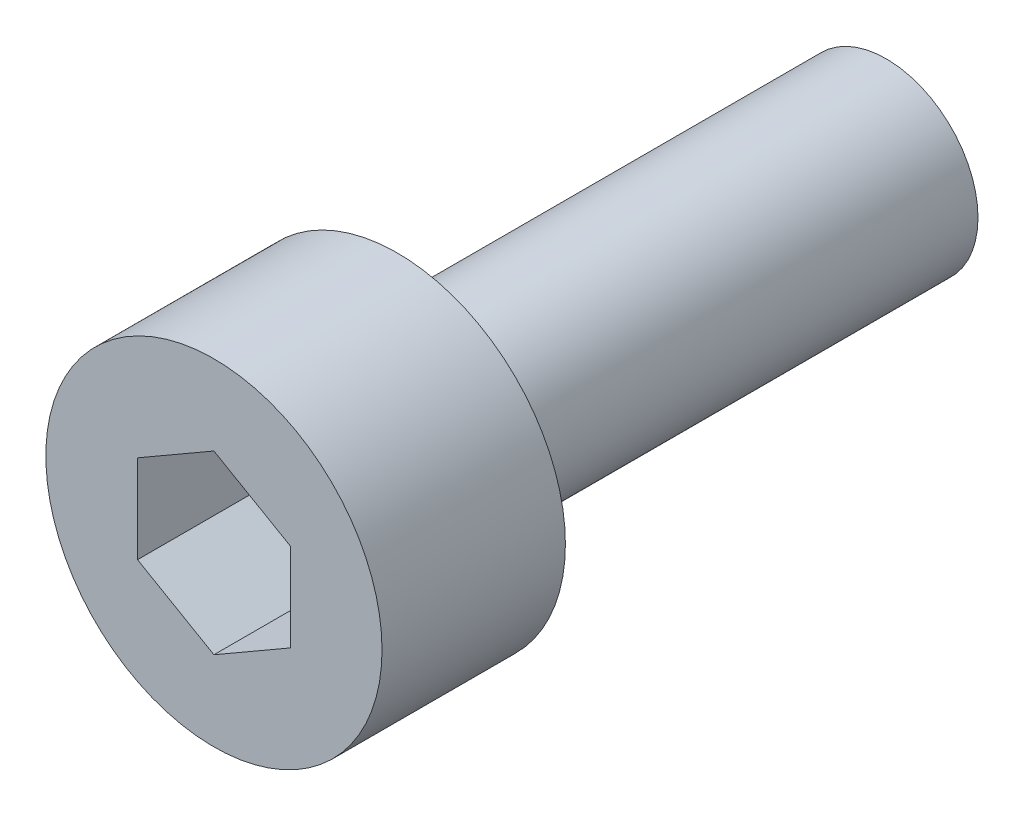
SolidWorks part; units mm, degrees
ref_plane "前视基准面" through (0, 0, 0) normal (0, 0, 1) x (1, 0, 0)
ref_plane "上视基准面" through (0, 0, 0) normal (0, 1, 0) x (1, 0, 0)
ref_plane "右视基准面" through (0, 0, 0) normal (1, 0, 0) x (0, 0, -1)
other "Configuration Table"
sketch "Profile_1" plane through (0, 0, 0) normal (0, 0, 1) x (1, 0, 0)
  circle A0 centre (0, 0) radius 1.5
extrude "Thread_envelope" add sketch "Profile_1" along normal blind 8 from offset 8
sketch "Profile_2" plane through (0, 0, 0) normal (0, 0, 1) x (1, 0, 0)
  line L0 (1.25, 0.7217) -> (0, 1.4434)
  line L1 (0, 1.4434) -> (-1.25, 0.7217)
  line L2 (-1.25, 0.7217) -> (-1.25, -0.7217)
  line L3 (-1.25, -0.7217) -> (0, -1.4434)
  line L4 (0, -1.4434) -> (1.25, -0.7217)
  line L5 (1.25, -0.7217) -> (1.25, 0.7217)
  circle A0 centre (0, 0) radius 2.75
extrude "Socket_head" add sketch "Profile_2" along normal blind 3 from offset 0
